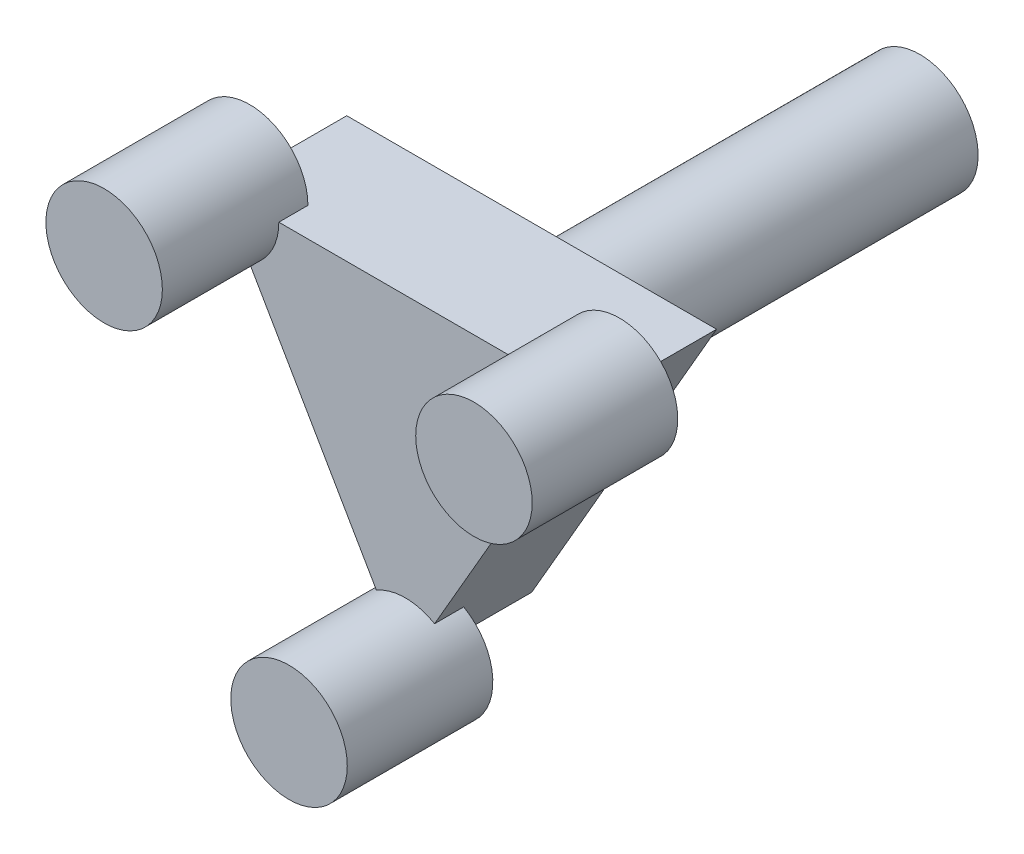
SolidWorks part; units mm, degrees
ref_plane "Front Plane" through (0, 0, 0) normal (0, 0, 1) x (1, 0, 0)
ref_plane "Top Plane" through (0, 0, 0) normal (0, 1, 0) x (1, 0, 0)
ref_plane "Right Plane" through (0, 0, 0) normal (1, 0, 0) x (0, 0, -1)
sketch "Sketch1" plane through (0, 0, 0) normal (0, 0, 1) x (1, 0, 0)
  circle A0 centre (0, -44) radius 6
  circle A3 centre (19.0526, -11) radius 6
  circle A4 centre (-19.0526, -11) radius 6
  point P0 (-18.436, -11)
  point P9 (0, 0)
  point P14 (0, 0)
extrude "Boss-Extrude1" add sketch "Sketch1" along normal blind 15
sketch "Sketch2" plane through (0, 0, 0) normal (0, 0, -1) x (-1, 0, 0)
  line L0 (-19.0526, -11) -> (0, -44)
  line L1 (0, -44) -> (19.0526, -11)
  line L2 (19.0526, -11) -> (-19.0526, -11)
extrude "Boss-Extrude2" add sketch "Sketch2" along normal blind 13 from offset 3 offset against normal yes
sketch "Sketch4" plane through (0, 0, -10) normal (0, 0, -1) x (-1, 0, 0)
  line L0 (0, -11) -> (0, -44) construction
  line L1 (19.0526, -11) -> (-19.0526, -11) construction
  line L2 (19.0526, -11) -> (-9.5263, -27.5) construction
  line L3 (-19.0526, -11) -> (0, -44) construction
  line L4 (-19.0526, -11) -> (9.5263, -27.5) construction
  line L5 (0, -44) -> (19.0526, -11) construction
  circle A0 centre (0, -22) radius 6
  point P15 (0, -22)
  dimension "D1" = 12
extrude "Boss-Extrude3" add sketch "Sketch4" along normal blind 40
